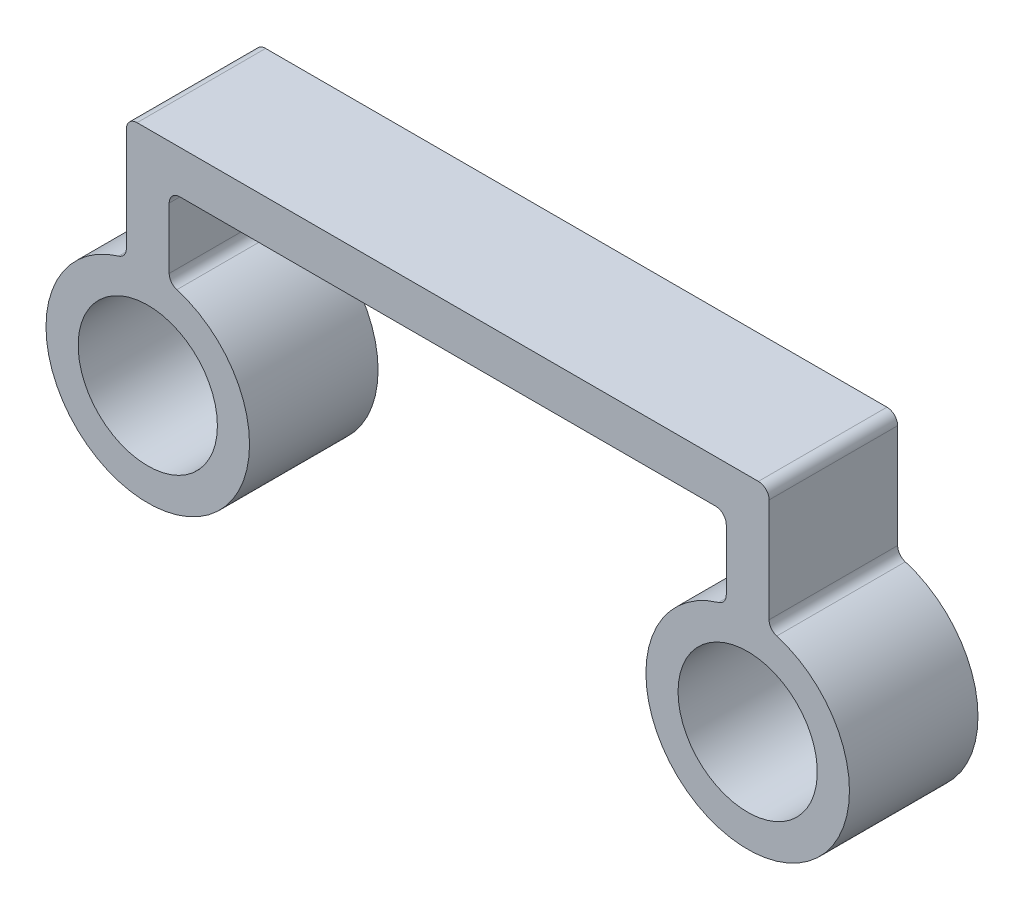
SolidWorks part; units mm, degrees
ref_plane "Front Plane" through (0, 0, 0) normal (0, 0, 1) x (1, 0, 0)
ref_plane "Top Plane" through (0, 0, 0) normal (0, 1, 0) x (1, 0, 0)
ref_plane "Right Plane" through (0, 0, 0) normal (1, 0, 0) x (0, 0, -1)
sketch "Sketch1" plane through (0, 0, 0) normal (0, 0, 1) x (1, 0, 0)
  line L4 (-28, 0) -> (-28, 25.7047) construction
  line L6 (-26, 9.2871) -> (-26, 16.75)
  line L7 (-26, 16.75) -> (0, 16.75)
  line L8 (-30, 9.2871) -> (-30, 20.75)
  line L9 (-30, 20.75) -> (0, 20.75)
  line L10 (0, 20.75) -> (0, 16.75)
  circle A0 centre (-28, 0) radius 6.5
  arc A2 (-30, 9.2871) -> (-26, 9.2871) centre (-28, 0) ccw
  point P0 (0, 18.75)
  dimension "D1" = 13
  dimension "D2" = 9.5
  dimension "D5" = 28
  dimension "D3" = 4
  dimension "D4" = 16.75
  dimension "D6" = 4
  dimension "D8" = 26
extrude "Boss-Extrude1" add sketch "Sketch1" along normal blind 12
mirror "Mirror1" about plane through (0, 0, 0) normal (1, 0, 0) of "Boss-Extrude1"
fillet "Fillet1" radius 1 8 edges at (-30, 9.2871, 6) (-26, 9.2871, 6) (26, 9.2871, 6) (30, 9.2871, 6) (26, 16.75, 6) (-26, 16.75, 6) (-30, 20.75, 6) (30, 20.75, 6)
sketch "Sketch2" plane through (0, 0, 12) normal (0, 0, 1) x (1, 0, 0)
  circle A0 centre (-28, 0) radius 6.5 construction
  circle A1 centre (28, 0) radius 6.5 construction
  circle A2 centre (28, 0) radius 6.5
  circle A3 centre (-28, 0) radius 6.5
  dimension "D1" = 56
